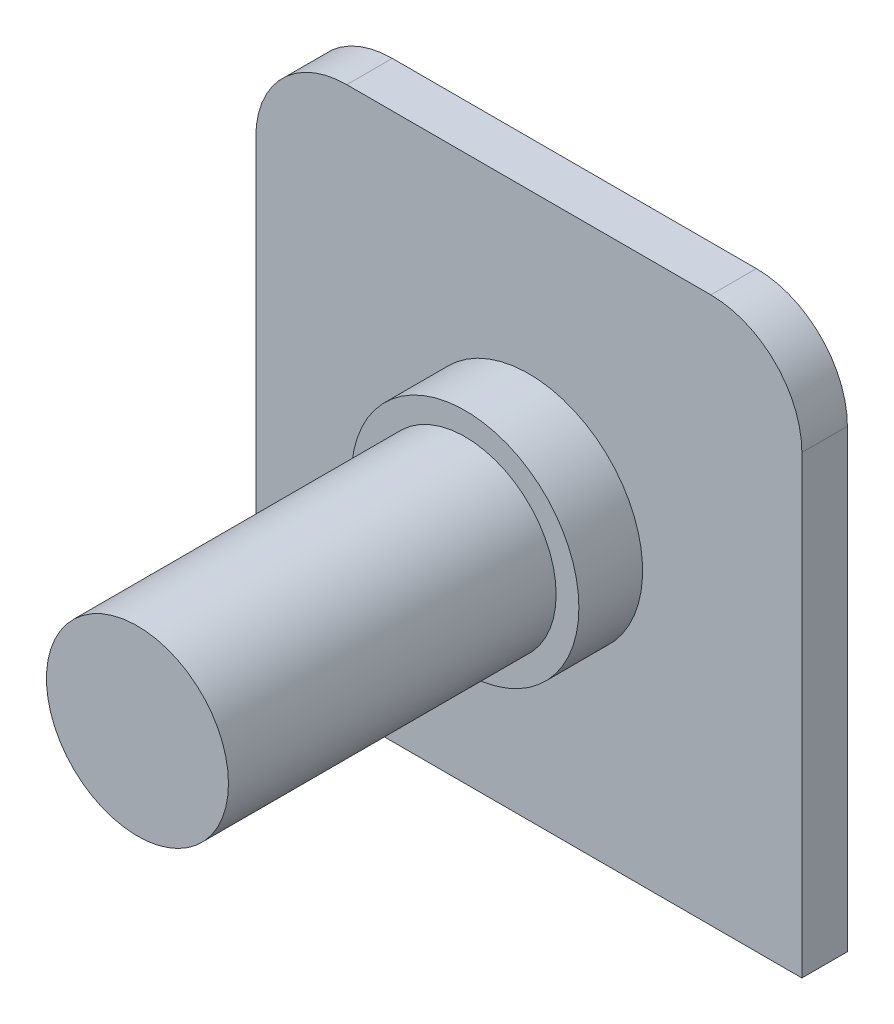
SolidWorks part; units mm, degrees
ref_plane "Front Plane" through (0, 0, 0) normal (0, 0, 1) x (1, 0, 0)
ref_plane "Top Plane" through (0, 0, 0) normal (0, 1, 0) x (1, 0, 0)
ref_plane "Right Plane" through (0, 0, 0) normal (1, 0, 0) x (0, 0, -1)
sketch "Sketch1" plane through (0, 0, 0) normal (0, 0, 1) x (1, 0, 0)
  line L9 (-762, -762) -> (762, -762)
  line L10 (-762, -762) -> (-762, 762)
  line L11 (-762, 762) -> (762, 762)
  line L12 (762, -762) -> (762, 762)
  line L13 (-762, -762) -> (762, 762) construction
  line L14 (-762, 762) -> (762, -762) construction
  point P0 (0, 0)
  dimension "D1" = 1524
  dimension "D2" = 1524
extrude "Boss-Extrude1" add sketch "Sketch1" along normal blind 127
sketch "Sketch2" plane through (0, 0, 127) normal (0, 0, 1) x (1, 0, 0)
  circle A0 centre (0, 0) radius 254
  dimension "D1" = 508
extrude "Boss-Extrude2" add sketch "Sketch2" along normal blind 1092.2
sketch "Sketch3" plane through (0, 0, 127) normal (0, 0, 1) x (1, 0, 0)
  circle A0 centre (0, 0) radius 317.5
  dimension "D1" = 635
extrude "Boss-Extrude3" add sketch "Sketch3" along normal blind 177.8
fillet "Fillet1" radius 254 2 edges at (762, 762, 63.5) (-762, 762, 63.5)
